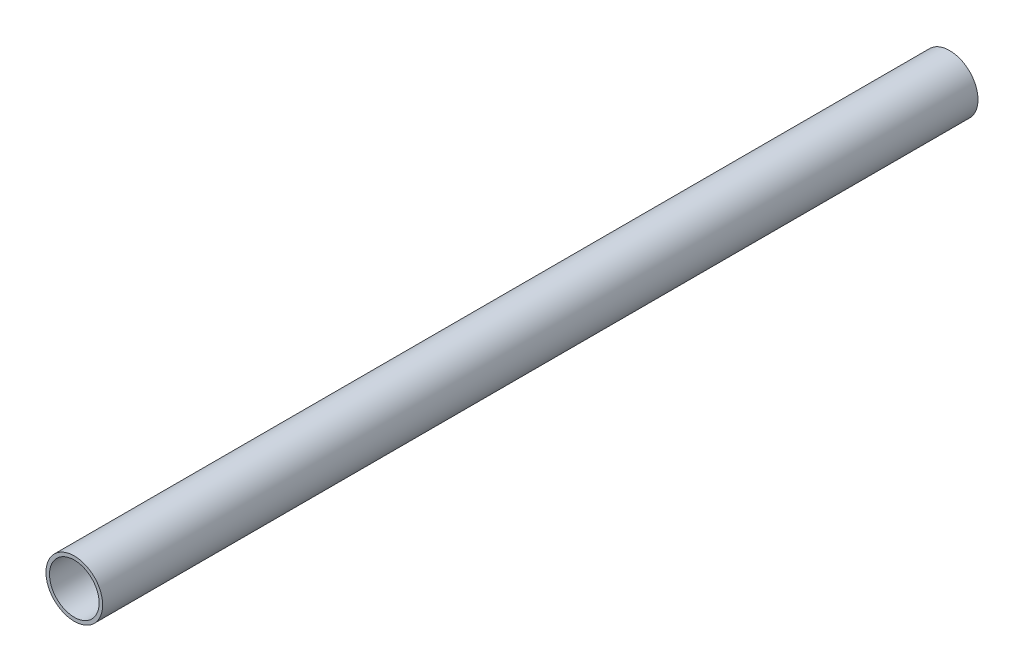
SolidWorks part; units mm, degrees
ref_plane "Front Plane" through (0, 0, 0) normal (0, 0, 1) x (1, 0, 0)
ref_plane "Top Plane" through (0, 0, 0) normal (0, 1, 0) x (1, 0, 0)
ref_plane "Right Plane" through (0, 0, 0) normal (1, 0, 0) x (0, 0, -1)
sketch "Sketch1" plane through (0, 0, 0) normal (0, 0, 1) x (1, 0, 0)
  circle A0 centre (0, 0) radius 7
  circle A1 centre (0, 0) radius 8
  dimension "D1" = 14
  dimension "D2" = 16
extrude "Boss-Extrude1" add sketch "Sketch1" along normal blind 247
